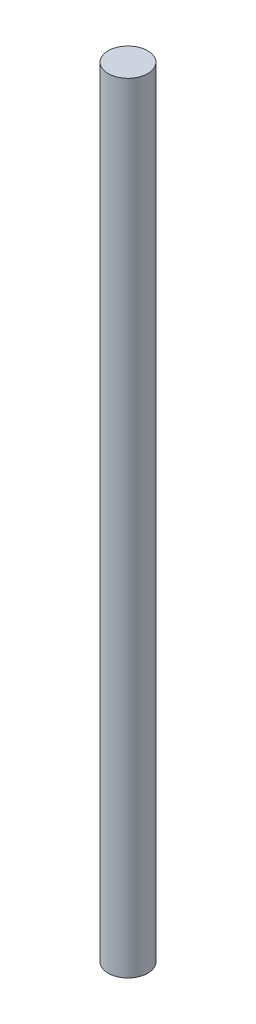
SolidWorks part; units mm, degrees
ref_plane "Front Plane" through (0, 0, 0) normal (0, 0, 1) x (1, 0, 0)
ref_plane "Top Plane" through (0, 0, 0) normal (0, 1, 0) x (1, 0, 0)
ref_plane "Right Plane" through (0, 0, 0) normal (1, 0, 0) x (0, 0, -1)
sketch "Sketch1" plane through (0, 0, 0) normal (0, 1, 0) x (1, 0, 0)
  circle A0 centre (0, 0) radius 12.7
  dimension "D1" = 25.4
extrude "Boss-Extrude1" add sketch "Sketch1" along normal blind 500
equation "\"carbon_fiber_tube_diam\"= 1in, 25.4mm"
equation "\"clip_tube_diam\"= 6mm"
equation "\"D1@Sketch1\"=\"carbon_fiber_tube_diam\""
equation "\"middle_tube_len\"= 500mm"
equation "\"D1@Boss-Extrude1\"=\"middle_tube_len\""
